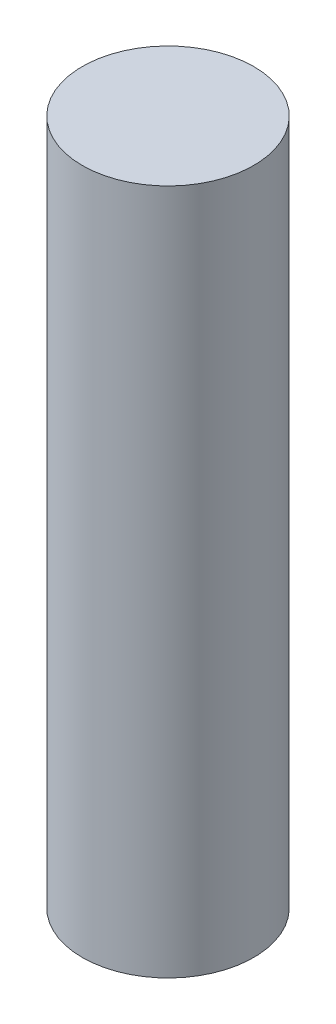
SolidWorks part; units mm, degrees
ref_plane "Front Plane" through (0, 0, 0) normal (0, 0, 1) x (1, 0, 0)
ref_plane "Top Plane" through (0, 0, 0) normal (0, 1, 0) x (1, 0, 0)
ref_plane "Right Plane" through (0, 0, 0) normal (1, 0, 0) x (0, 0, -1)
sketch "Sketch2" plane through (0, 0, 0) normal (0, 1, 0) x (1, 0, 0)
  circle A0 centre (0, 0) radius 93.75
extrude "Boss-Extrude1" add sketch "Sketch2" along normal blind 750
